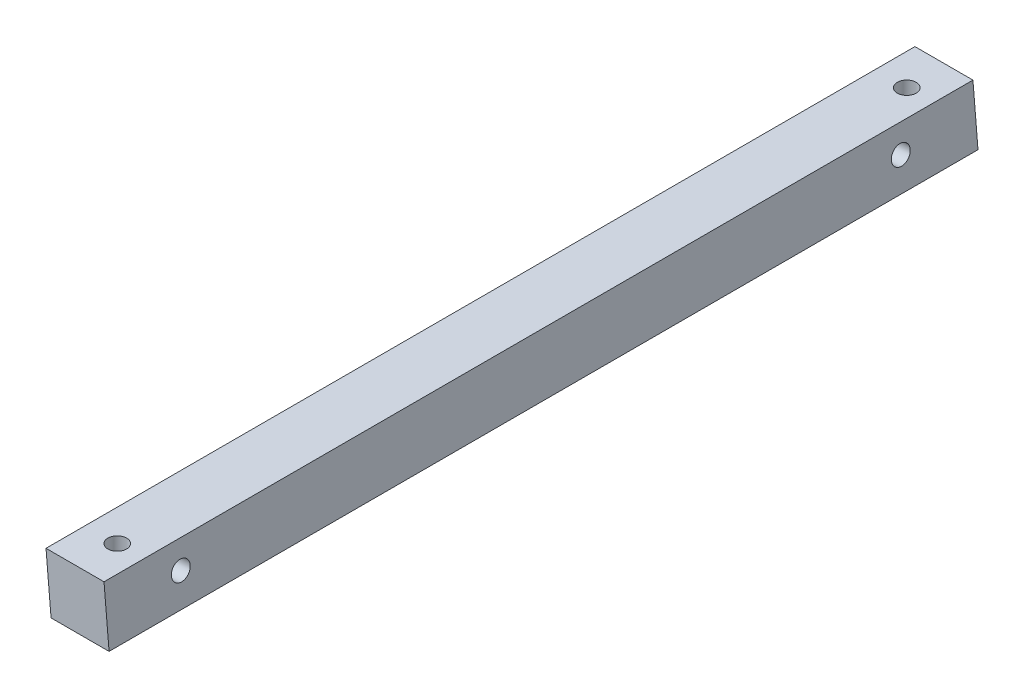
SolidWorks part; units mm, degrees
ref_plane "Front Plane" through (0, 0, 0) normal (0, 0, 1) x (1, 0, 0)
ref_plane "Top Plane" through (0, 0, 0) normal (0, 1, 0) x (1, 0, 0)
ref_plane "Right Plane" through (0, 0, 0) normal (1, 0, 0) x (0, 0, -1)
sketch "Sketch1" plane through (0, 0, 0) normal (0, 0, 1) x (1, 0, 0)
  line L0 (0, 0) -> (11.6819, 0)
  line L1 (11.6819, 0) -> (10.6637, 11.6374)
  line L2 (10.6637, 11.6374) -> (-1.0181, 11.6374)
  line L3 (-1.0181, 11.6374) -> (0, 0)
  dimension "D1" = 12.7
  dimension "D2" = 85
extrude "Boss-Extrude1" add sketch "Sketch1" along normal blind 175
sketch "Sketch2" plane through (0, 0, 0) normal (0, 1, 0) x (1, 0, 0)
  line L0 (-1.0181, 0) -> (11.6819, 0) construction
  line L1 (5.3319, 0) -> (5.3319, -175) construction
  line L2 (10.6637, -175) -> (-1.0181, -175) construction
  circle A0 centre (5.3319, -8) radius 1.9
  circle A1 centre (5.3319, -167) radius 1.9
  dimension "D1" = 3.8
  dimension "D2" = 8
  dimension "D3" = 8
extrude "Cut-Extrude1" cut sketch "Sketch2" along normal through all
sketch "Sketch3" plane through (11.5931, 1.0143, 0) normal (0.9962, 0.0872, 0) x (0, 0, -1)
  line L0 (-175, -1.0181) -> (-175, 11.6819) construction
  line L1 (-175, 5.3319) -> (0, 5.3319) construction
  line L2 (0, -1.0181) -> (0, 10.6637) construction
  circle A0 centre (-160, 5.3319) radius 1.9
  circle A1 centre (-15, 5.3319) radius 1.9
  dimension "D2" = 3.8
  dimension "D1" = 15
  dimension "D3" = 15
extrude "Cut-Extrude2" cut sketch "Sketch3" against normal through all both and the other way through all
equation "\"D3@Sketch2\"=\"D2@Sketch2\""
equation "\"D3@Sketch3\"=\"D1@Sketch3\""
